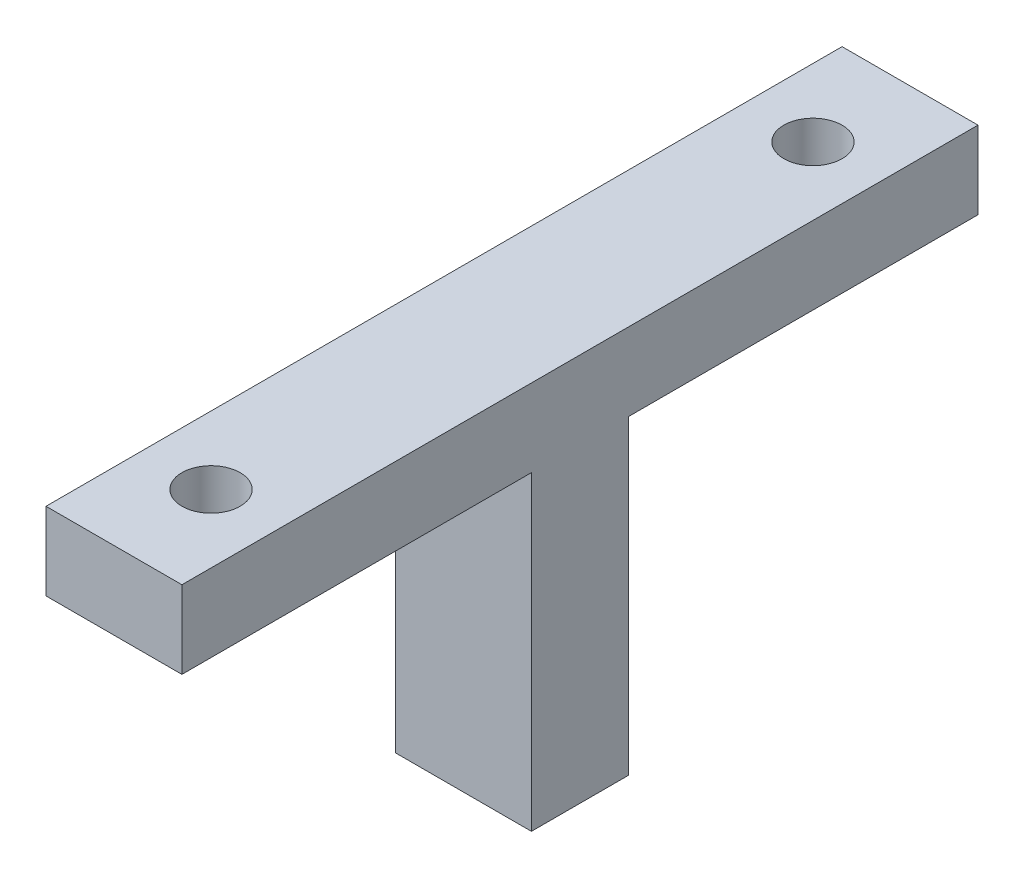
SolidWorks part; units mm, degrees
ref_plane "Front Plane" through (0, 0, 0) normal (0, 0, 1) x (1, 0, 0)
ref_plane "Top Plane" through (0, 0, 0) normal (0, 1, 0) x (1, 0, 0)
ref_plane "Right Plane" through (0, 0, 0) normal (1, 0, 0) x (0, 0, -1)
sketch "Sketch1" plane through (0, 0, 0) normal (0, 1, 0) x (1, 0, 0)
  line L1 (-3.5, 2.5) -> (3.5, 2.5)
  line L2 (-3.5, 2.5) -> (-3.5, -2.5)
  line L3 (-3.5, -2.5) -> (3.5, -2.5)
  line L4 (3.5, 2.5) -> (3.5, -2.5)
  line L5 (-3.5, 2.5) -> (3.5, -2.5) construction
  line L6 (-3.5, -2.5) -> (3.5, 2.5) construction
  point P0 (0, 0)
  dimension "D1" = 5
  dimension "D2" = 7
extrude "Boss-Extrude1" add sketch "Sketch1" along normal blind 20
sketch "Sketch2" plane through (0, 0, 2.5) normal (0, 0, 1) x (1, 0, 0)
  line L0 (3.5, 20) -> (3.5, 0) construction
  line L1 (-3.5, 20) -> (3.5, 20)
  line L2 (-3.5, 20) -> (-3.5, 16)
  line L3 (-3.5, 16) -> (3.5, 16)
  line L4 (3.5, 20) -> (3.5, 16)
  dimension "D1" = 4
extrude "Boss-Extrude2" add sketch "Sketch2" along normal blind 18
hole_wizard "Ø3.0mm Dowel Hole1" positions "Sketch5" profile "Sketch6" hole size "Ø3.0" standard "ANSI Metric" end condition through all
sketch "Sketch5" plane through (0, 20, 0) normal (0, 1, 0) x (1, 0, 0)
  line L1 (3.5, -20.5) -> (-3.5, -20.5) construction
  point P0 (0, -15.5)
  dimension "D1" = 5
sketch "Sketch6" plane through (0, 20, 15.5) normal (1, 0, 0) x (0, 0, 1)
  line L0 (0, 0) -> (0, 20)
  line L1 (0, 20) -> (1.5, 20)
  line L2 (1.5, 20) -> (1.5, 0)
  line L5 (1.5, 0) -> (0, 0)
  line L11 (0, -6.35) -> (0, 107.95) construction
  dimension "Thru Hole Dia." = 3
  dimension "Thru Hole Depth" = 20
mirror "Mirror1" about plane through (0, 0, 0) normal (0, 0, 1) of "Boss-Extrude2", "Ø3.0mm Dowel Hole1"
